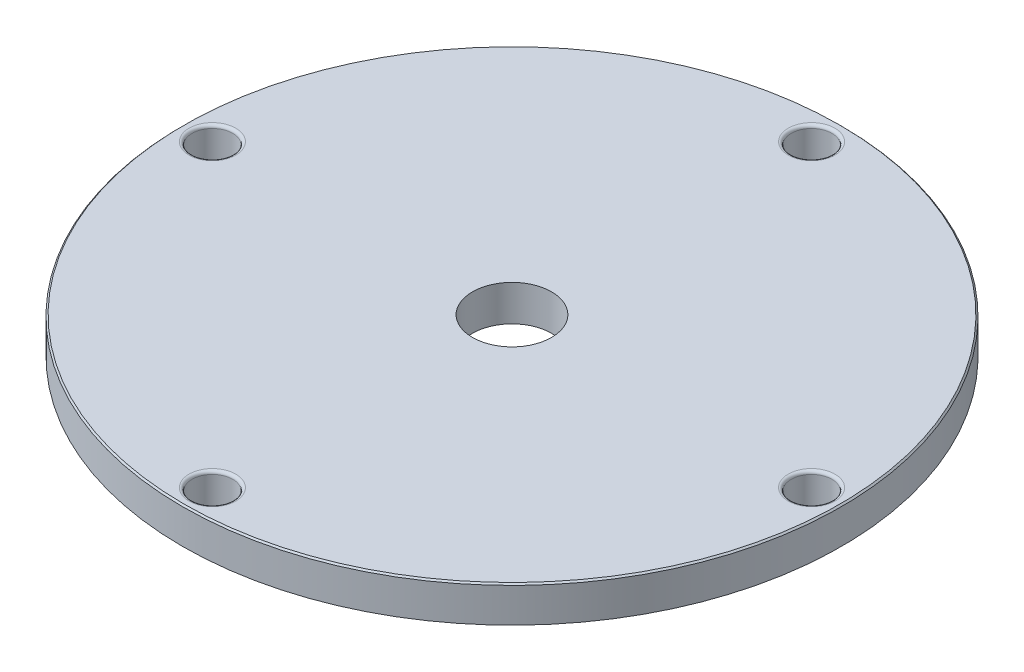
SolidWorks part; units mm, degrees
ref_plane "Front Plane" through (0, 0, 0) normal (0, 0, 1) x (1, 0, 0)
ref_plane "Top Plane" through (0, 0, 0) normal (0, 1, 0) x (1, 0, 0)
ref_plane "Right Plane" through (0, 0, 0) normal (1, 0, 0) x (0, 0, -1)
sketch "Sketch1" plane through (0, 0, 0) normal (0, 1, 0) x (1, 0, 0)
  line L0 (0, 0) -> (-16.9203, 16.9203)
  circle A0 centre (0, 0) radius 27.5
  circle A1 centre (0, 0) radius 3.3
  dimension "D1" = 6.6
  dimension "D2" = 55
extrude "Boss-Extrude1" add sketch "Sketch1" along normal blind 3
sketch "Sketch2" plane through (0, 3, 0) normal (0, 1, 0) x (1, 0, 0)
  line L0 (0, 0) -> (0, 25)
  circle A0 centre (0, 25) radius 1.7
  circle A1 centre (25, 0) radius 1.7
  circle A2 centre (0, -25) radius 1.7
  circle A3 centre (-25, 0) radius 1.7
  point P13 (0, 0)
  dimension "D2" = 3.4
  dimension "D1" = 25
  dimension "D3" = 4
extrude "Cut-Extrude1" cut sketch "Sketch2" against normal through all contours A3 | A2 | A1 | A0
chamfer "Chamfer1" distance 0.125 angle 45 1 edges at (0, 3, 27.5)
fillet "Fillet1" radius 0.25 4 edges at (-25, 3, 1.7) (0, 3, 26.7) (25, 3, 1.7) (0, 3, -23.3)
